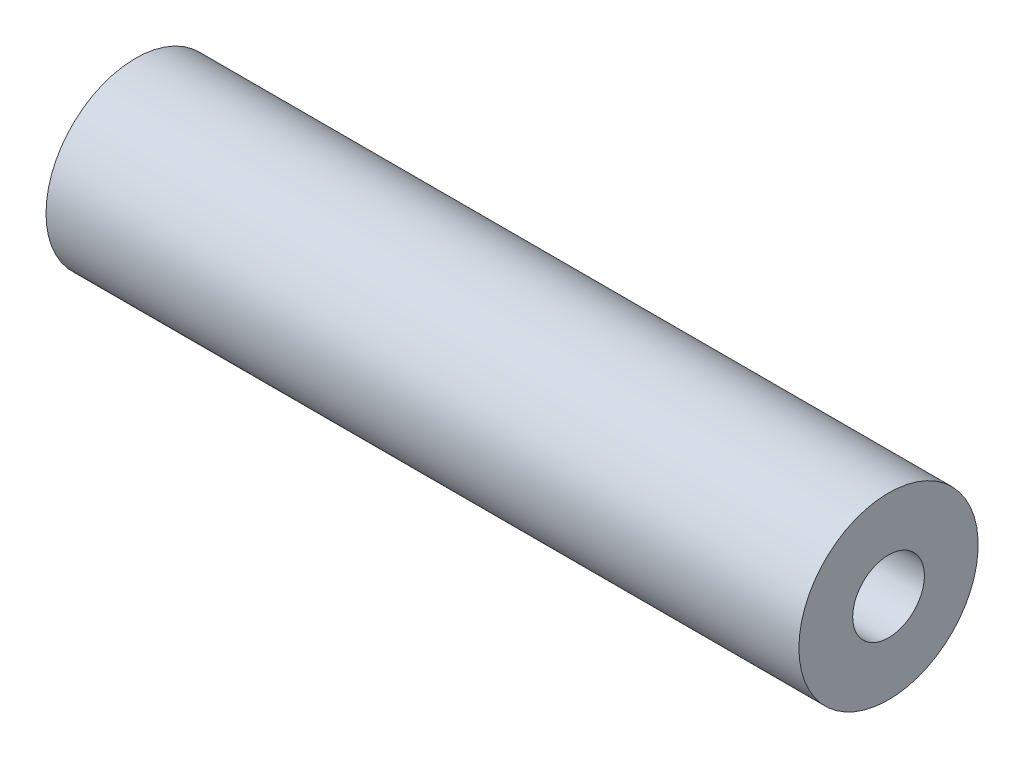
SolidWorks part; units mm, degrees
ref_plane "前视基准面" through (0, 0, 0) normal (0, 0, 1) x (1, 0, 0)
ref_plane "上视基准面" through (0, 0, 0) normal (0, 1, 0) x (1, 0, 0)
ref_plane "右视基准面" through (0, 0, 0) normal (1, 0, 0) x (0, 0, -1)
sketch "草图1" plane through (0, 0, 0) normal (1, 0, 0) x (0, 0, -1)
  circle A0 centre (0, 0) radius 2
  circle A1 centre (0, 0) radius 5
  dimension "D1" = 4
  dimension "D2" = 10
extrude "凸台-拉伸1" add sketch "草图1" along normal mid plane 42
